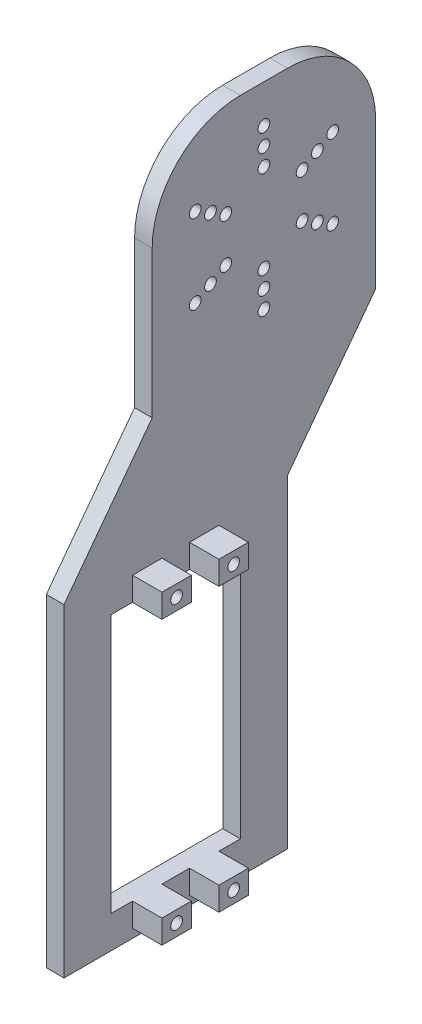
SolidWorks part; units mm, degrees
material "Polylactic Acid"
ref_plane "Front Plane" through (0, 0, 0) normal (0, 0, 1) x (1, 0, 0)
ref_plane "Top Plane" through (0, 0, 0) normal (0, 1, 0) x (1, 0, 0)
ref_plane "Right Plane" through (0, 0, 0) normal (1, 0, 0) x (0, 0, -1)
sketch "Sketch1" plane through (0, 0, 0) normal (1, 0, 0) x (0, 0, -1)
  line L0 (-19, -27.5) -> (19, -27.5)
  line L1 (19, -27.5) -> (19, 27.5)
  line L2 (19, 27.5) -> (34, 47.5)
  line L3 (34, 47.5) -> (34, 87.5)
  line L4 (34, 87.5) -> (-4, 87.5)
  line L5 (-4, 87.5) -> (-4, 47.5)
  line L6 (-4, 47.5) -> (-19, 27.5)
  line L7 (-19, 27.5) -> (-19, -27.5)
  line L8 (-4.85, -24) -> (4.85, -24) construction
  line L9 (-4.85, -24) -> (-4.85, 24) construction
  line L10 (15, 75) -> (15, 78) construction
  line L11 (-11, 22) -> (11, 22)
  line L12 (-11, 22) -> (-11, -22)
  line L13 (-11, -22) -> (11, -22)
  line L14 (11, 22) -> (11, -22)
  line L15 (21.4952, 71.25) -> (24.0933, 72.75) construction
  line L16 (21.4952, 63.75) -> (24.0933, 62.25) construction
  line L21 (15, 60) -> (15, 57) construction
  line L22 (8.5048, 63.75) -> (5.9067, 62.25) construction
  line L23 (8.5048, 71.25) -> (5.9067, 72.75) construction
  line L24 (15, 67.5) -> (15, 75) construction
  circle A0 centre (-4.85, -24) radius 1
  circle A1 centre (4.85, -24) radius 1
  circle A2 centre (4.85, 24) radius 1
  circle A3 centre (-4.85, 24) radius 1
  circle A8 centre (15, 75) radius 1
  circle A9 centre (15, 78) radius 1
  circle A10 centre (15, 81) radius 1
  circle A11 centre (21.4952, 71.25) radius 1
  circle A12 centre (24.0933, 72.75) radius 1
  circle A13 centre (26.6913, 74.25) radius 1
  circle A14 centre (21.4952, 63.75) radius 1
  circle A15 centre (24.0933, 62.25) radius 1
  circle A16 centre (26.6913, 60.75) radius 1
  circle A17 centre (15, 60) radius 1
  circle A18 centre (15, 57) radius 1
  circle A19 centre (15, 54) radius 1
  circle A20 centre (8.5048, 63.75) radius 1
  circle A21 centre (5.9067, 62.25) radius 1
  circle A22 centre (3.3087, 60.75) radius 1
  circle A23 centre (8.5048, 71.25) radius 1
  circle A24 centre (5.9067, 72.75) radius 1
  circle A25 centre (3.3087, 74.25) radius 1
  point P23 (-11, 0)
  point P24 (-4.85, 0)
  point P25 (0, -24)
  point P26 (0, -22)
  point P28 (0, -27.5)
  point P29 (-19, 0)
  point P49 (15, 87.5)
  point P86 (-4, 67.5)
  dimension "D1" = 2
  dimension "D16" = 6
  dimension "D15" = 2
  dimension "D4" = 9.7
  dimension "D5" = 48
  dimension "D6" = 22
  dimension "D7" = 44
  dimension "D8" = 38
  dimension "D9" = 55
  dimension "D10" = 15
  dimension "D11" = 20
  dimension "D14" = 3
  dimension "D17" = 7.5
  dimension "D12" = 40
  dimension "D13" = 3
  dimension "D2" = 2
  dimension "D3" = 2
extrude "Boss-Extrude1" add sketch "Sketch1" along normal mid plane 3
fillet "Fillet1" radius 15 2 edges at (0, 87.5, -34) (0, 87.5, 4)
sketch "Sketch2" plane through (1.5, 0, 0) normal (1, 0, 0) x (0, 0, -1)
  line L0 (-11, -22) -> (11, -22) construction
  line L1 (-7.35, -26) -> (-2.35, -26)
  line L2 (-7.35, -26) -> (-7.35, -22)
  line L3 (-7.35, -22) -> (-2.35, -22)
  line L4 (-2.35, -26) -> (-2.35, -22)
  line L5 (-7.35, -26) -> (-2.35, -22) construction
  line L6 (-7.35, -22) -> (-2.35, -26) construction
  line L7 (2.35, -26) -> (7.35, -26)
  line L8 (2.35, -26) -> (2.35, -22)
  line L9 (2.35, -22) -> (7.35, -22)
  line L10 (7.35, -26) -> (7.35, -22)
  line L11 (2.35, -26) -> (7.35, -22) construction
  line L12 (2.35, -22) -> (7.35, -26) construction
  line L13 (2.35, 22) -> (7.35, 22)
  line L14 (2.35, 22) -> (2.35, 26)
  line L15 (2.35, 26) -> (7.35, 26)
  line L16 (7.35, 22) -> (7.35, 26)
  line L17 (2.35, 22) -> (7.35, 26) construction
  line L18 (2.35, 26) -> (7.35, 22) construction
  line L19 (-7.35, 22) -> (-2.35, 22)
  line L20 (-7.35, 22) -> (-7.35, 26)
  line L21 (-7.35, 26) -> (-2.35, 26)
  line L22 (-2.35, 22) -> (-2.35, 26)
  line L23 (-7.35, 22) -> (-2.35, 26) construction
  line L24 (-7.35, 26) -> (-2.35, 22) construction
  line L25 (-4.85, -24) -> (4.85, -24) construction
  line L26 (-4.85, -24) -> (-4.85, 24) construction
  line L28 (-4.85, -24) -> (4.85, -24) construction
  line L29 (-4.85, -24) -> (-4.85, 24) construction
  circle A0 centre (4.85, 24) radius 1 construction
  circle A1 centre (-4.85, -24) radius 1
  circle A2 centre (-4.85, -24) radius 1 construction
  circle A3 centre (4.85, -24) radius 1
  circle A4 centre (4.85, 24) radius 1
  circle A5 centre (-4.85, 24) radius 1
  point P0 (-4.85, -24)
  point P9 (4.85, -24)
  point P15 (4.85, 24)
  point P20 (-4.85, 24)
  point P28 (1.248, -24)
  point P29 (0, 0)
  dimension "D1" = 5
  dimension "D4" = 2
  dimension "D5" = 2
  dimension "D2" = 2
  dimension "D3" = 2
extrude "Boss-Extrude2" add sketch "Sketch2" along normal blind 5
